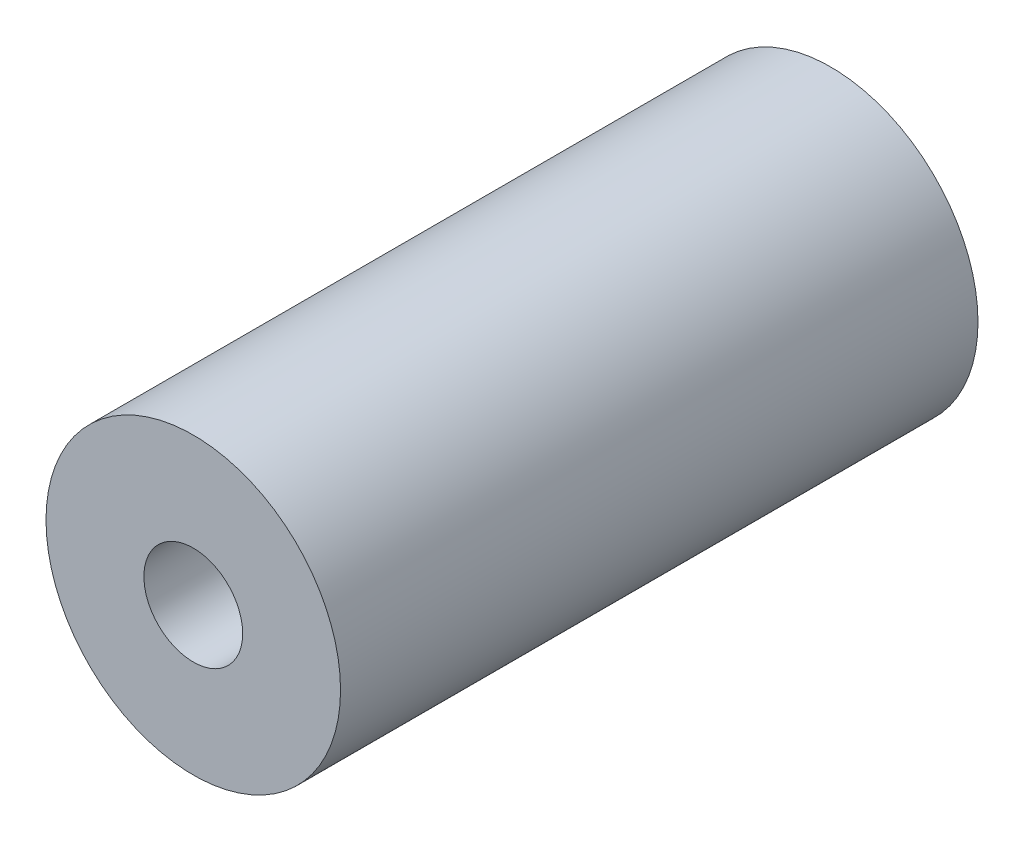
SolidWorks part; units mm, degrees
ref_plane "Front" through (0, 0, 0) normal (0, 0, 1) x (1, 0, 0)
ref_plane "Top" through (0, 0, 0) normal (0, 1, 0) x (1, 0, 0)
ref_plane "Right" through (0, 0, 0) normal (1, 0, 0) x (0, 0, -1)
sketch "Sketch1" plane through (0, 0, 0) normal (0, 0, 1) x (1, 0, 0)
  circle A1 centre (0, 0) radius 16.7
extrude "Extrude1" add sketch "Sketch1" along normal up to surface (36.143 mm away) and the other way up to surface (36.143 mm away)
sketch "Sketch2" plane through (0, 0, 0) normal (0, 0, 1) x (1, 0, 0)
  circle A0 centre (0, 0) radius 15.875
  dimension "D1" = 31.75
extrude "STROKE CHAMBER" cut sketch "Sketch2" along normal up to surface and the other way up to surface
sketch "Sketch3" plane through (0, 0, 36.143) normal (0, 0, 1) x (1, 0, 0)
  circle A0 centre (0, 0) radius 5.6
  dimension "D1" = 11.2
extrude "ROD HOLE" cut sketch "Sketch3" against normal up to next
